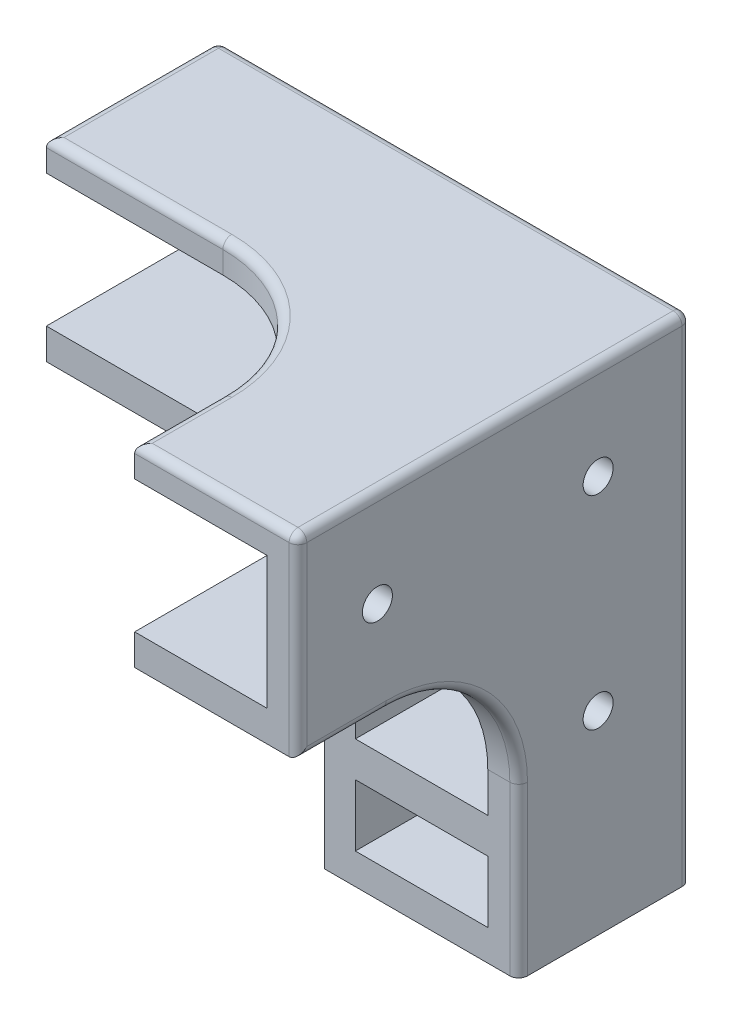
SolidWorks part; units mm, degrees
ref_plane "Front Plane" through (0, 0, 0) normal (0, 0, 1) x (1, 0, 0)
ref_plane "Top Plane" through (0, 0, 0) normal (0, 1, 0) x (1, 0, 0)
ref_plane "Right Plane" through (0, 0, 0) normal (1, 0, 0) x (0, 0, -1)
sketch "Sketch1" plane through (0, 0, 0) normal (0, 0, 1) x (1, 0, 0)
  line L1 (-5.6994, 32.9163) -> (16.3006, 32.9163)
  line L2 (-5.6994, 10.9163) -> (-5.6994, -23.0837)
  line L3 (-5.6994, -23.0837) -> (16.3006, -23.0837)
  line L4 (16.3006, 32.9163) -> (16.3006, -23.0837)
  line L5 (-5.6994, 10.9163) -> (-37.1994, 10.9163)
  line L7 (-5.6994, 32.9163) -> (-37.1994, 32.9163)
  line L8 (-37.1994, 10.9163) -> (-37.1994, 32.9163)
  dimension "D1" = 22
  dimension "D2" = 22
  dimension "D3" = 56
  dimension "D4" = 53.5
extrude "Boss-Extrude1" add sketch "Sketch1" along normal blind 19.5
sketch "Sketch3" plane through (0, 0, 19.5) normal (0, 0, 1) x (1, 0, 0)
  line L1 (16.3006, 32.9163) -> (-2.1994, 32.9163)
  line L2 (16.3006, 32.9163) -> (16.3006, 10.9163)
  line L3 (16.3006, 10.9163) -> (-2.1994, 10.9163)
  line L4 (-2.1994, 32.9163) -> (-2.1994, 10.9163)
  dimension "D1" = 18.5
  dimension "D2" = 22
extrude "Boss-Extrude2" add sketch "Sketch3" along normal blind 25
sketch "Sketch5" plane through (0, 0, 44.5) normal (0, 0, 1) x (1, 0, 0)
  line L0 (-37.1994, 32.9163) -> (-37.1994, 10.9163) construction
  line L1 (-37.1994, 29.4163) -> (12.8006, 29.4163)
  line L2 (-37.1994, 29.4163) -> (-37.1994, 14.4163)
  line L3 (-37.1994, 14.4163) -> (12.8006, 14.4163)
  line L4 (12.8006, 29.4163) -> (12.8006, 14.4163)
  line L5 (16.3006, 10.9163) -> (16.3006, 32.9163) construction
  line L6 (-2.1994, 6.4163) -> (12.8006, 6.4163)
  line L7 (-2.1994, 6.4163) -> (-2.1994, -8.5837)
  line L8 (-2.1994, -8.5837) -> (12.8006, -8.5837)
  line L9 (12.8006, 6.4163) -> (12.8006, -8.5837)
  line L12 (-2.1994, 32.9163) -> (-37.1994, 32.9163) construction
  line L13 (-2.1994, 10.9163) -> (16.3006, 10.9163) construction
  line L15 (16.3006, -23.0837) -> (16.3006, 10.9163) construction
  line L16 (-5.6994, -23.0837) -> (16.3006, -23.0837) construction
  line L17 (-2.1994, -12.5837) -> (12.8006, -12.5837)
  line L18 (-2.1994, -12.5837) -> (-2.1994, -19.5837)
  line L19 (-2.1994, -19.5837) -> (12.8006, -19.5837)
  line L20 (12.8006, -12.5837) -> (12.8006, -19.5837)
  dimension "D1" = 3.5
  dimension "D2" = 4.5
  dimension "D3" = 15
  dimension "D4" = 3.5
  dimension "D5" = 15
  dimension "D6" = 15
  dimension "D7" = 3.5
  dimension "D8" = 15
  dimension "D9" = 4
  dimension "D10" = 3.5
extrude "Cut-Extrude1" cut sketch "Sketch5" against normal offset from surface (40.5 mm away) 4 up to face at (-8.8661, 6.9163, 0)
sketch "Sketch7" plane through (16.3006, 0, 0) normal (1, 0, 0) x (0, 0, -1)
  line L0 (-34.5, 10.9163) -> (-19.5, 10.9163)
  line L1 (-44.5, 10.9163) -> (-19.5, 10.9163) construction
  line L2 (-19.5, 10.9163) -> (-19.5, -4.0837)
  line L3 (-19.5, -23.0837) -> (-19.5, 10.9163) construction
  arc A0 (-34.5, 10.9163) -> (-19.5, -4.0837) centre (-34.5, -4.0837) cw
  dimension "D1" = 15
extrude "Boss-Extrude4" add sketch "Sketch7" against normal blind 3.5
sketch "Sketch8" plane through (0, 0, 0) normal (0, 0, -1) x (-1, 0, 0)
  line L0 (5.6994, 10.9163) -> (20.6994, 10.9163)
  line L1 (37.1994, 10.9163) -> (5.6994, 10.9163) construction
  line L2 (5.6994, 10.9163) -> (5.6994, -4.0837)
  line L3 (5.6994, 10.9163) -> (5.6994, -23.0837) construction
  arc A0 (20.6994, 10.9163) -> (5.6994, -4.0837) centre (20.6994, -4.0837) ccw
  dimension "D1" = 15
extrude "Boss-Extrude5" add sketch "Sketch8" against normal blind 3.5
sketch "Sketch9" plane through (0, 32.9163, 0) normal (0, 1, 0) x (1, 0, 0)
  line L0 (-2.1994, -34.5) -> (-2.1994, -19.5)
  line L1 (-2.1994, -44.5) -> (-2.1994, -19.5) construction
  line L2 (-2.1994, -19.5) -> (-17.1994, -19.5)
  line L3 (-2.1994, -19.5) -> (-37.1994, -19.5) construction
  arc A0 (-2.1994, -34.5) -> (-17.1994, -19.5) centre (-17.1994, -34.5) ccw
  dimension "D1" = 15
extrude "Boss-Extrude6" add sketch "Sketch9" against normal blind 3.5
fillet "Fillet3" radius 3 1 edges
sketch "Sketch11" plane through (0, 0, 0) normal (0, 0, -1) x (-1, 0, 0)
  line L0 (1.1994, -23.0837) -> (1.1994, 10.9163) construction
  line L2 (5.6994, -23.0837) -> (-16.3006, -23.0837) construction
  line L5 (5.6994, -4.0837) -> (5.6994, -23.0837) construction
  text T0 "MR.3" font "Century Gothic" height 12
  dimension "D1" = 4.5
extrude "Cut-Extrude3" cut sketch "Sketch11" against normal blind 1
sketch "Sketch12" plane through (0, 0, 0) normal (0, 0, -1) x (-1, 0, 0)
  line L0 (37.1994, 21.9163) -> (-16.3006, 21.9163) construction
  line L1 (37.1994, 32.9163) -> (37.1994, 10.9163) construction
  line L2 (-16.3006, -23.0837) -> (-16.3006, 32.9163) construction
  line L3 (-12.8006, 14.4163) -> (-12.8006, 29.4163) construction
  circle A0 centre (-5.3006, 21.9163) radius 1.7
  circle A1 centre (10.9494, 21.9163) radius 1.7
  circle A2 centre (27.1994, 21.9163) radius 1.7
  dimension "D4" = 3.4
  dimension "D1" = 7.5
  dimension "D2" = 10
  dimension "D3" = 16.25
extrude "Cut-Extrude4" cut sketch "Sketch12" against normal blind 5
sketch "Sketch13" plane through (-5.6994, 0, 0) normal (-1, 0, 0) x (0, 0, 1)
  line L0 (4, 6.4163) -> (19.5, 6.4163) construction
  line L1 (19.5, 10.9163) -> (19.5, -23.0837) construction
  circle A0 centre (10.5, -1.0837) radius 1.7
  dimension "D2" = 9
  dimension "D3" = 3.4
  dimension "D1" = 7.5
extrude "Cut-Extrude5" cut sketch "Sketch13" against normal blind 45
sketch "Sketch14" plane through (16.3006, 0, 0) normal (1, 0, 0) x (0, 0, -1)
  line L0 (-10.5, -1.0837) -> (-10.5, 32.9163) construction
  line L1 (-44.5, 32.9163) -> (0, 32.9163) construction
  line L2 (-44.5, 21.9163) -> (-10.5, 21.9163) construction
  line L3 (-44.5, 10.9163) -> (-44.5, 32.9163) construction
  circle A0 centre (-10.5, 21.9163) radius 1.7
  circle A1 centre (-35.5, 21.9163) radius 1.7
  dimension "D1" = 3.4
  dimension "D2" = 9
extrude "Cut-Extrude6" cut sketch "Sketch14" against normal blind 45
sketch "Sketch15" plane through (0, -23.0837, 0) normal (0, -1, 0) x (1, 0, 0)
  line L0 (16.3006, 9.75) -> (-5.6994, 9.75) construction
  line L1 (16.3006, 19.5) -> (16.3006, 0) construction
  line L2 (-5.6994, 19.5) -> (-5.6994, 0) construction
  line L3 (5.3006, 19.5) -> (5.3006, 0) construction
  line L4 (-5.6994, 19.5) -> (16.3006, 19.5) construction
  line L5 (-5.6994, 0) -> (16.3006, 0) construction
  circle A0 centre (5.3006, 9.75) radius 1.7
  dimension "D1" = 3.4
extrude "Cut-Extrude7" cut sketch "Sketch15" against normal blind 4
fillet "Fillet4" radius 1 16 edges at (-5.6994, -13.5837, 0) (-10.0928, 6.5229, 0) (-6.5928, 32.9163, 23.8934) (16.3006, 32.9163, 22.25) (-37.1994, 32.9163, 9.75) (16.3006, 21.9163, 44.5) (7.0506, 32.9163, 44.5) (-10.4494, 32.9163, 0) (16.3006, 4.9163, 0) (-28.9494, 10.9163, 0) (-37.1994, 21.9163, 0) (16.3006, 6.5229, 23.8934)
